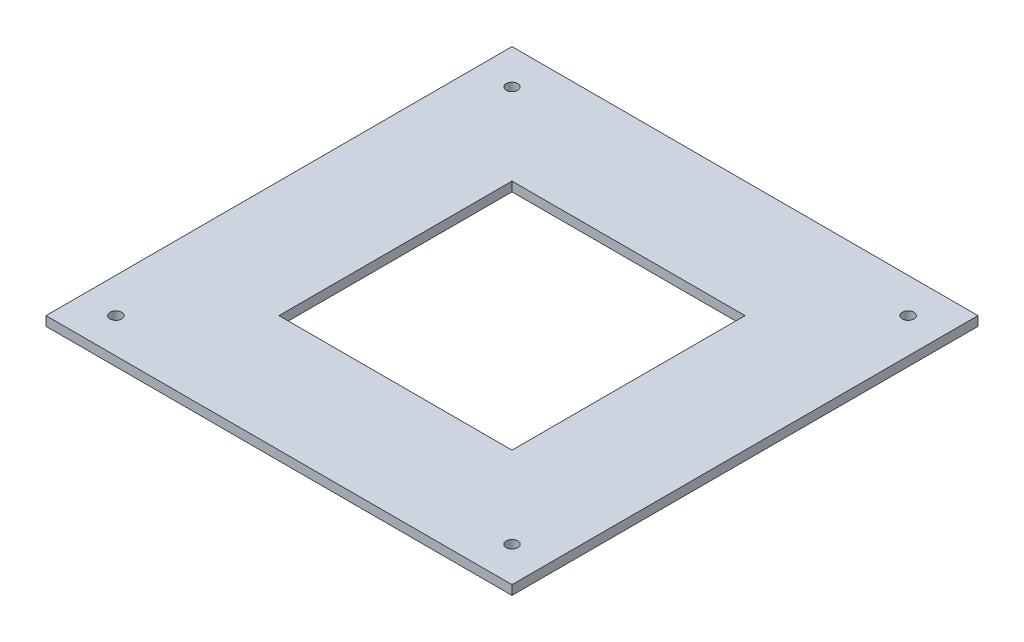
SolidWorks part; units mm, degrees
ref_plane "Alzado" through (0, 0, 0) normal (0, 0, 1) x (1, 0, 0)
ref_plane "Planta" through (0, 0, 0) normal (0, 1, 0) x (1, 0, 0)
ref_plane "Vista lateral" through (0, 0, 0) normal (1, 0, 0) x (0, 0, -1)
sketch "Croquis1" plane through (0, 0, 0) normal (0, 1, 0) x (1, 0, 0)
  line L0 (100, 15) -> (100, 0) construction
  line L1 (0, 0) -> (200, 0)
  line L2 (0, 0) -> (0, 200)
  line L3 (0, 200) -> (200, 200)
  line L4 (200, 0) -> (200, 200)
  line L5 (15, 15) -> (185, 15) construction
  line L6 (15, 15) -> (15, 185) construction
  line L7 (15, 185) -> (185, 185) construction
  line L8 (185, 15) -> (185, 185) construction
  line L9 (185, 100) -> (200, 100) construction
  circle A0 centre (15, 185) radius 2.5
  circle A1 centre (185, 185) radius 2.5
  circle A2 centre (185, 15) radius 2.5
  circle A3 centre (15, 15) radius 2.5
  dimension "D3" = 5
  dimension "D1" = 200
  dimension "D2" = 170
extrude "Saliente-Extruir1" add sketch "Croquis1" along normal blind 4
sketch "Croquis2" plane through (0, 4, 0) normal (0, 1, 0) x (1, 0, 0)
  line L0 (50, 100) -> (0, 100) construction
  line L1 (50, 50) -> (150, 50)
  line L2 (50, 50) -> (50, 150)
  line L3 (50, 150) -> (150, 150)
  line L4 (150, 50) -> (150, 150)
  line L5 (0, 200) -> (0, 0) construction
  line L6 (100, 50) -> (100, 0) construction
  line L7 (0, 0) -> (200, 0) construction
  line L8 (50, 100) -> (150, 100) construction
  line L9 (100, 150) -> (100, 50) construction
  line L10 (23, 126.5) -> (23, 100) construction
  line L19 (25, 25) -> (175, 25) construction
  line L20 (25, 25) -> (25, 175) construction
  line L21 (25, 175) -> (175, 175) construction
  line L22 (175, 25) -> (175, 175) construction
  line L27 (100, 150) -> (100, 173) construction
  line L29 (50, 150.0904) -> (100, 150.0904) construction
  line L30 (25, 136.5) -> (27, 136.5) construction
  line L59 (27, 100) -> (27, 173) construction
  line L60 (27, 173) -> (100, 173) construction
  line L62 (63.5, 173) -> (63.5, 175) construction
  point P18 (25, 100)
  point P19 (100, 175)
  dimension "D1" = 100
  dimension "D2" = 150
  dimension "D6" = 73
extrude "Cortar-Extruir1" cut sketch "Croquis2" against normal blind 4
